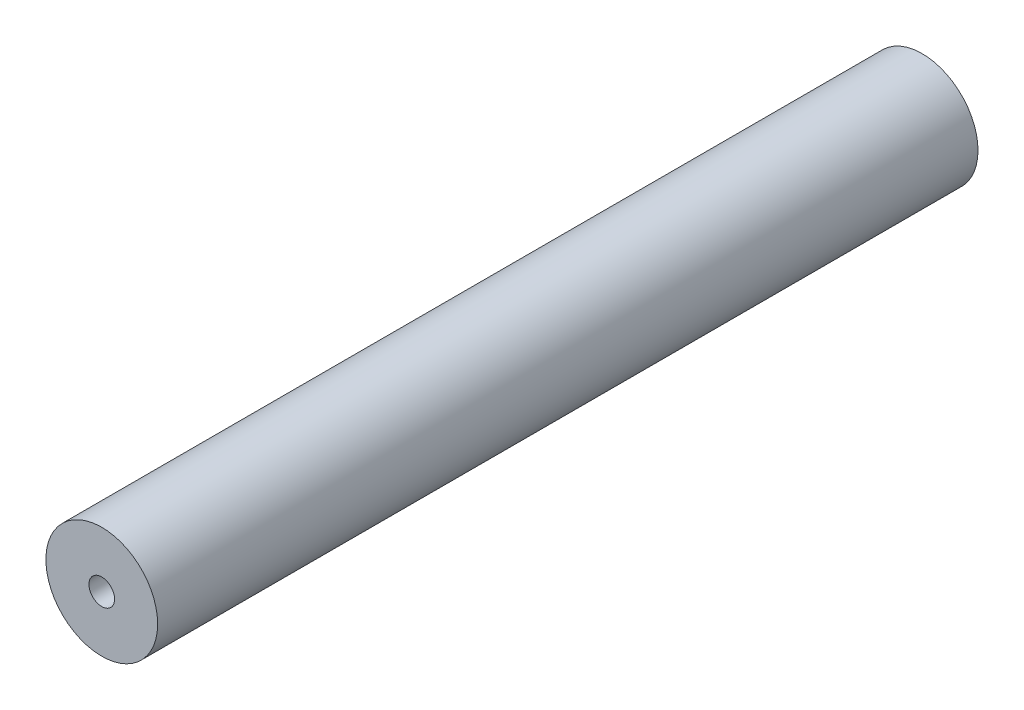
SolidWorks part; units mm, degrees
ref_plane "Front Plane" through (0, 0, 0) normal (0, 0, 1) x (1, 0, 0)
ref_plane "Top Plane" through (0, 0, 0) normal (0, 1, 0) x (1, 0, 0)
ref_plane "Right Plane" through (0, 0, 0) normal (1, 0, 0) x (0, 0, -1)
sketch "Sketch1" plane through (0, 0, 0) normal (0, 0, 1) x (1, 0, 0)
  circle A0 centre (0, 0) radius 13.839
extrude "Boss-Extrude1" add sketch "Sketch1" along normal blind 203.2
hole_wizard "1/4 (0.25) Diameter Hole1" positions "Sketch2" profile "Sketch3" hole size "1/4" standard "ANSI Inch" end condition through all
sketch "Sketch2" plane through (0, 0, 203.2) normal (0, 0, 1) x (1, 0, 0)
  point P0 (0, 0)
sketch "Sketch3" plane through (0, 0, 203.2) normal (1, 0, 0) x (0, -1, 0)
  line L0 (0, 0) -> (0, 203.2)
  line L1 (0, 203.2) -> (3.175, 203.2)
  line L2 (3.175, 203.2) -> (3.175, 0)
  line L5 (3.175, 0) -> (0, 0)
  line L11 (0, -6.35) -> (0, 107.95) construction
  dimension "Thru Hole Dia." = 6.35
  dimension "Thru Hole Depth" = 203.2
